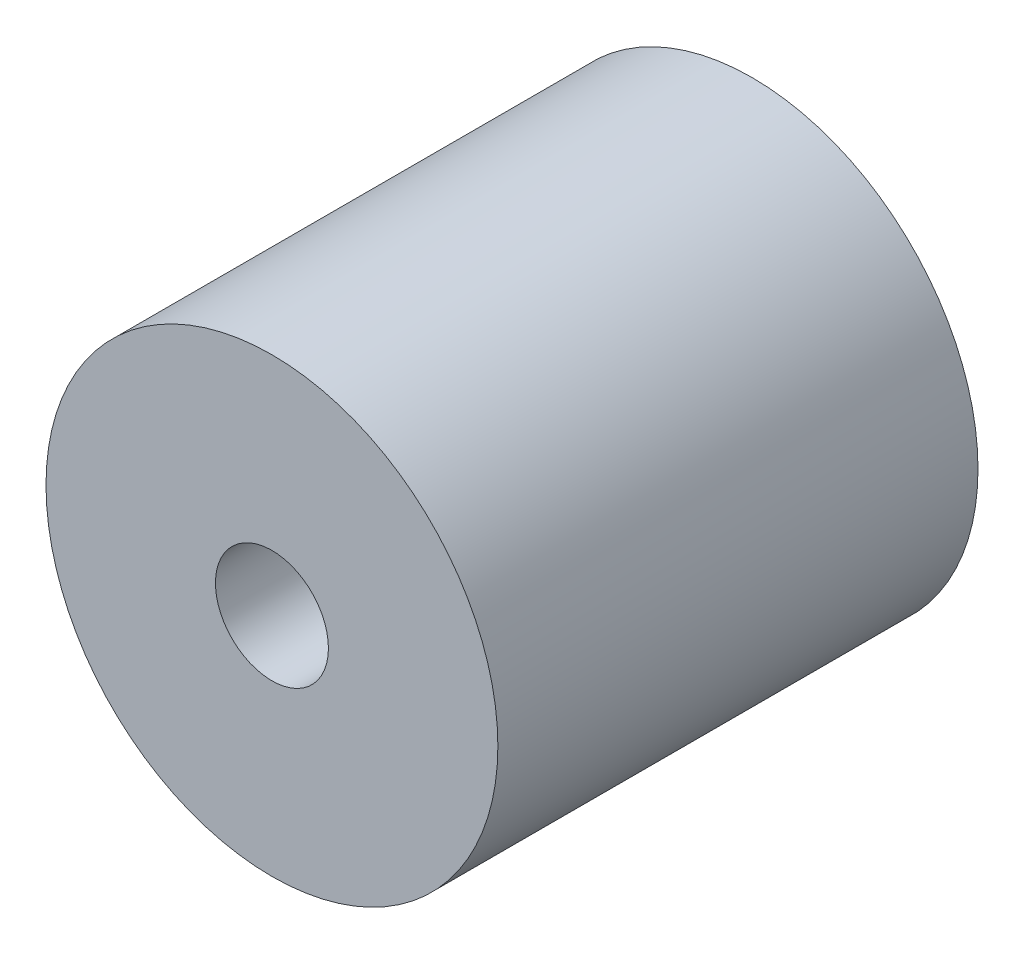
SolidWorks part; units mm, degrees
ref_plane "Alzado" through (0, 0, 0) normal (0, 0, 1) x (1, 0, 0)
ref_plane "Planta" through (0, 0, 0) normal (0, 1, 0) x (1, 0, 0)
ref_plane "Vista lateral" through (0, 0, 0) normal (1, 0, 0) x (0, 0, -1)
sketch "Croquis1" plane through (0, 0, 0) normal (0, 0, 1) x (1, 0, 0)
  circle A0 centre (0, 0) radius 4
  dimension "D1" = 8
extrude "Saliente-Extruir1" add sketch "Croquis1" along normal blind 8.5
sketch "Croquis2" plane through (0, 0, 8.5) normal (0, 0, 1) x (1, 0, 0)
  circle A0 centre (0, 0) radius 1
  dimension "D1" = 2
extrude "Cortar-Extruir1" cut sketch "Croquis2" against normal through all
